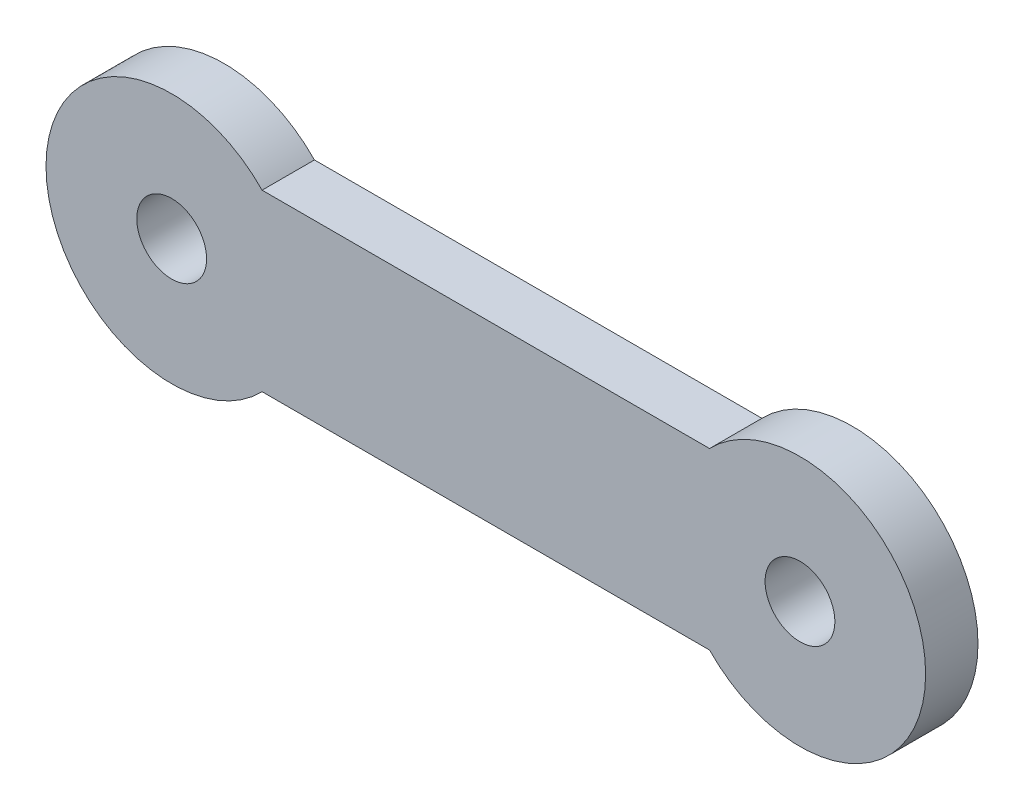
SolidWorks part; units mm, degrees
ref_plane "Front" through (0, 0, 0) normal (0, 0, 1) x (1, 0, 0)
ref_plane "Top" through (0, 0, 0) normal (0, 1, 0) x (1, 0, 0)
ref_plane "Right" through (0, 0, 0) normal (1, 0, 0) x (0, 0, -1)
sketch "Croquis1" plane through (0, 0, 0) normal (0, 0, 1) x (1, 0, 0)
  line L0 (0, 0) -> (18, 0) construction
  line L3 (2.5904, -2.5) -> (15.4096, -2.5)
  line L5 (2.5904, 2.5) -> (15.4096, 2.5)
  line L7 (4.7529, -1.9856) -> (14.3474, 2.5) construction
  line L8 (4.7529, 1.9856) -> (14.3474, -2.5) construction
  arc A0 (2.5904, 2.5) -> (2.5904, -2.5) centre (0, 0) ccw
  arc A1 (15.4096, -2.5) -> (15.4096, 2.5) centre (18, 0) ccw
  point P4 (9, 0)
  dimension "D1" = 7.2
  dimension "D2" = 18
  dimension "D3" = 5
extrude "Saliente-Extruir1" add sketch "Croquis1" along normal blind 1.5
sketch "Croquis2" plane through (0, 0, 1.5) normal (0, 0, 1) x (1, 0, 0)
  circle A0 centre (0, 0) radius 1
  circle A1 centre (18, 0) radius 1
  arc A2 (15.4096, -2.5) -> (15.4096, 2.5) centre (18, 0) ccw construction
  dimension "D1" = 2
extrude "Cortar-Extruir1" cut sketch "Croquis2" against normal blind 1.5
